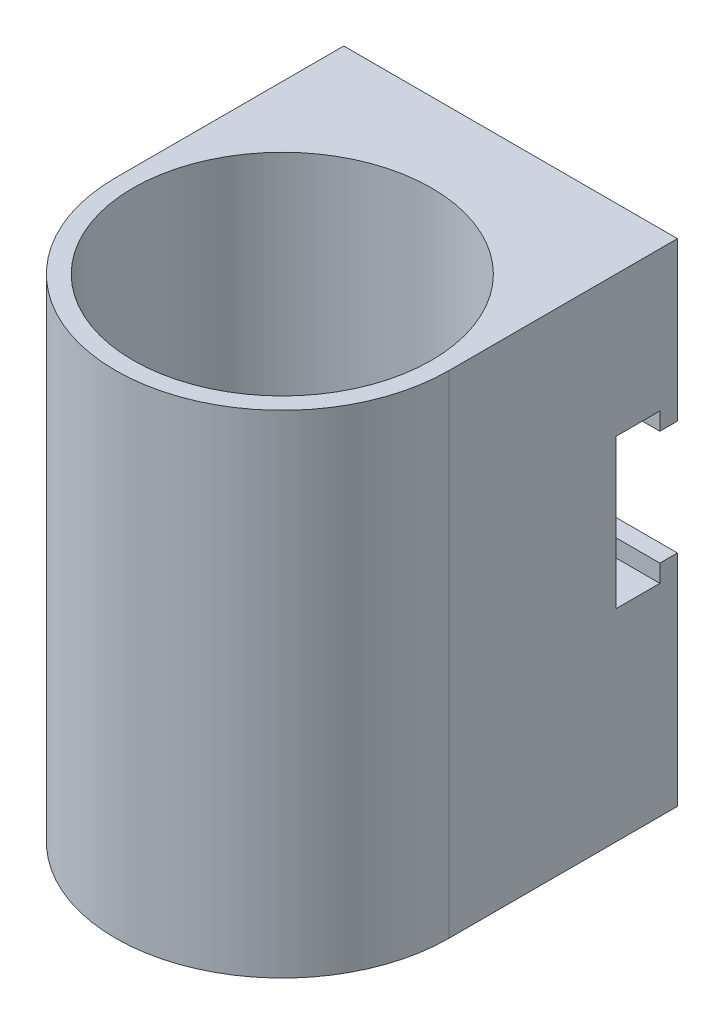
SolidWorks part; units mm, degrees
ref_plane "Front Plane" through (0, 0, 0) normal (0, 0, 1) x (1, 0, 0)
ref_plane "Top Plane" through (0, 0, 0) normal (0, 1, 0) x (1, 0, 0)
ref_plane "Right Plane" through (0, 0, 0) normal (1, 0, 0) x (0, 0, -1)
sketch "Sketch1" plane through (0, 0, 0) normal (0, 1, 0) x (1, 0, 0)
  line L0 (-15.0813, 0) -> (-15.0813, 20.6375)
  line L1 (-15.0813, 20.6375) -> (15.0813, 20.6375)
  line L2 (15.0813, 20.6375) -> (15.0813, 0)
  circle A0 centre (0, 0) radius 13.4938
  circle A1 centre (0, 0) radius 15.0813 construction
  arc A2 (-15.0813, 0) -> (15.0813, 0) centre (0, 0) ccw
  dimension "D1" = 26.9875
  dimension "D2" = 1.5875
  dimension "D3" = 20.6375
extrude "Boss-Extrude1" add sketch "Sketch1" along normal blind 44.45
sketch "Sketch2" plane through (0, 0, 0) normal (0, -1, 0) x (1, 0, 0)
  circle A0 centre (0, 0) radius 15.0813
  dimension "D1" = 30.1625
extrude "Boss-Extrude2" add sketch "Sketch2" against normal blind 1.5875
sketch "Sketch3" plane through (15.0813, 0, 0) normal (1, 0, 0) x (0, 0, -1)
  line L0 (20.6375, 30.1625) -> (19.05, 30.1625)
  line L1 (20.6375, 44.45) -> (20.6375, 0) construction
  line L2 (19.05, 30.1625) -> (19.05, 31.75)
  line L3 (19.05, 31.75) -> (15.0813, 31.75)
  line L4 (15.0813, 31.75) -> (15.0813, 18.2563)
  line L5 (15.0813, 18.2563) -> (19.05, 18.2563)
  line L6 (19.05, 18.2563) -> (19.05, 19.8438)
  line L7 (19.05, 19.8438) -> (20.6375, 19.8438)
  line L8 (20.6375, 19.8438) -> (20.6375, 30.1625)
  line L9 (0, 44.45) -> (20.6375, 44.45) construction
  dimension "D1" = 1.5875
  dimension "D2" = 3.9688
  dimension "D3" = 13.4937
  dimension "D4" = 1.5875
  dimension "D5" = 12.7
extrude "Cut-Extrude1" cut sketch "Sketch3" against normal through all
